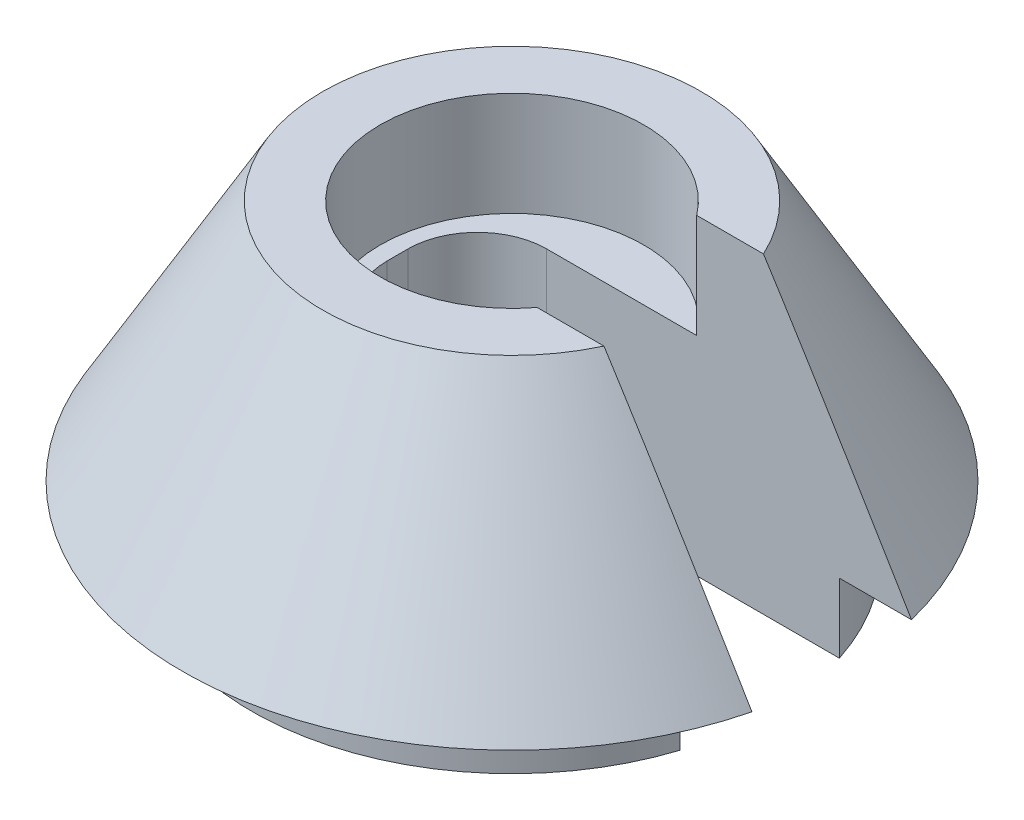
SolidWorks part; units mm, degrees
ref_plane "前视基准面" through (0, 0, 0) normal (0, 0, 1) x (1, 0, 0)
ref_plane "上视基准面" through (0, 0, 0) normal (0, 1, 0) x (1, 0, 0)
ref_plane "右视基准面" through (0, 0, 0) normal (1, 0, 0) x (0, 0, -1)
sketch "草图1" plane through (0, 0, 0) normal (0, 1, 0) x (1, 0, 0)
  circle A0 centre (0, 0) radius 7.5
  dimension "D1" = 15
extrude "凸台-拉伸1" add sketch "草图1" along normal blind 2
sketch "草图2" plane through (0, 2, 0) normal (0, 1, 0) x (1, 0, 0)
  circle A0 centre (0, 0) radius 9.5
  dimension "D1" = 19
extrude "凸台-拉伸2" add sketch "草图2" along normal blind 7 draft 30
sketch "草图4" plane through (0, 9, 0) normal (0, 1, 0) x (1, 0, 0)
  circle A0 centre (0, 0) radius 3.8
  dimension "D1" = 7.6
extrude "切除-拉伸1" cut sketch "草图4" against normal blind 3
sketch "草图5" plane through (0, 0, 0) normal (0, -1, 0) x (-1, 0, 0)
  line L1 (1.3, -2.3) -> (-11.8876, -2.3)
  line L2 (3.3, -0.3) -> (3.3, 0.3)
  line L3 (1.3, 2.3) -> (-11.8876, 2.3)
  line L4 (-11.8876, -2.3) -> (-11.8876, 2.3)
  circle A0 centre (0, 0) radius 7.5 construction
  arc A1 (1.3, 2.3) -> (3.3, 0.3) centre (1.3, 0.3) cw
  arc A2 (1.3, -2.3) -> (3.3, -0.3) centre (1.3, -0.3) ccw
  point P8 (3.3, 2.3)
  point P11 (3.3, -2.3)
  dimension "D4" = 2
  dimension "D5" = 2
  dimension "D1" = 2.3
  dimension "D2" = 2.3
  dimension "D3" = 3.3
extrude "切除-拉伸2" cut sketch "草图5" against normal through all
